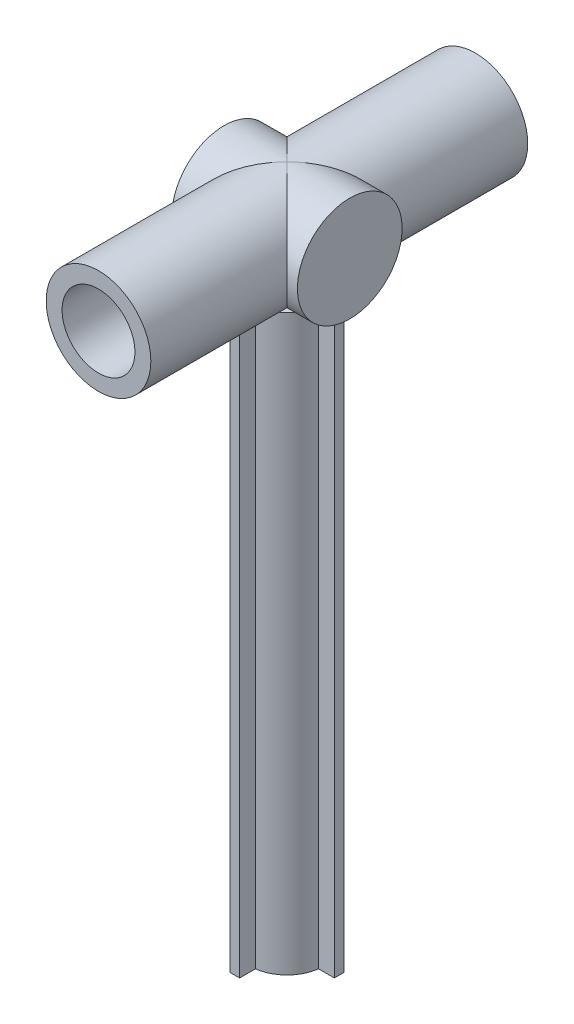
SolidWorks part; units mm, degrees
material "PVC Rigid"
ref_plane "Front Plane" through (0, 0, 0) normal (0, 0, 1) x (1, 0, 0)
ref_plane "Top Plane" through (0, 0, 0) normal (0, 1, 0) x (1, 0, 0)
ref_plane "Right Plane" through (0, 0, 0) normal (1, 0, 0) x (0, 0, -1)
sketch "Sketch3" plane through (0, 0, 0) normal (0, 1, 0) x (1, 0, 0)
  line L4 (-0.5802, 4.407) -> (-0.5802, 6.3234)
  line L5 (0.5802, 4.407) -> (0.5802, 6.3234)
  line L6 (0.5802, 6.3234) -> (-0.5802, 6.3234)
  line L7 (4.407, 0.5802) -> (6.3234, 0.5802)
  line L8 (4.407, -0.5802) -> (6.3234, -0.5802)
  line L9 (6.3234, -0.5802) -> (6.3234, 0.5802)
  line L10 (0.5802, -4.407) -> (0.5802, -6.3234)
  line L11 (0.5802, -6.3234) -> (-0.5802, -6.3234)
  line L12 (-0.5802, -4.407) -> (-0.5802, -6.3234)
  line L13 (-4.407, -0.5802) -> (-6.3234, -0.5802)
  line L14 (-6.3234, -0.5802) -> (-6.3234, 0.5802)
  line L15 (-4.407, 0.5802) -> (-6.3234, 0.5802)
  arc A8 (-0.5802, 4.407) -> (-4.407, 0.5802) centre (0, 0) ccw
  arc A9 (0.5802, 4.407) -> (4.407, 0.5802) centre (0, 0) cw
  arc A10 (4.407, -0.5802) -> (0.5802, -4.407) centre (0, 0) cw
  arc A11 (-0.5802, -4.407) -> (-4.407, -0.5802) centre (0, 0) cw
  circle A12 centre (0, 0) radius 2.794 construction
extrude "Boss-Extrude2" add sketch "Sketch3" along normal blind 69.596
sketch "Sketch4" plane through (0, 69.596, 0) normal (0, 1, 0) x (1, 0, 0)
  circle A0 centre (0, 0) radius 2.794
extrude "Cut-Extrude1" cut sketch "Sketch4" against normal through all
ref_plane "Plane1" through (0, 0, 0) normal (0, 0, 1) x (1, 0, 0)
sketch "Sketch5" plane through (0, 0, 0) normal (0, 0, 1) x (1, 0, 0)
  line L0 (4.407, 69.596) -> (0.5802, 69.596) construction
  circle A0 centre (0, 75.946) radius 6.35
  dimension "D1" = 6.35
  dimension "D2" = 12.7
extrude "Boss-Extrude3" add sketch "Sketch5" along normal blind 22.86 and the other way blind 22.86 separate body
sketch "Sketch6" plane through (0, 0, 22.86) normal (0, 0, 1) x (1, 0, 0)
  circle A0 centre (0, 75.946) radius 3.7382
mirror "Mirror1" about plane through (0, 0, 0) normal (0, 0, 1) of bodies 104 105
extrude "Cut-Extrude3" cut sketch "Sketch6" against normal blind 12.7
mirror "Mirror2" about plane through (0, 0, 0) normal (0, 0, 1) of bodies 107
ref_plane "Plane2" through (0, 0, 0) normal (1, 0, 0) x (0, 0, -1)
sketch "Sketch7" plane through (0, 0, 0) normal (1, 0, 0) x (0, 0, -1)
  line L0 (0, 8.382) -> (0, -8.382) construction
  line L1 (-0.5802, 69.596) -> (-4.407, 69.596) construction
  circle A0 centre (0, 75.946) radius 6.35
  dimension "D1" = 12.7
  dimension "D2" = 6.35
extrude "Boss-Extrude4" add sketch "Sketch7" along normal blind 7.62 and the other way blind 7.62
sketch "Sketch8" plane through (0, 0, 22.86) normal (0, 0, 1) x (1, 0, 0)
  circle A0 centre (0, 75.946) radius 4.4195
  dimension "D1" = 8.839
extrude "Cut-Extrude4" cut sketch "Sketch8" against normal blind 10.16
ref_plane "Plane3" through (0, 0, 0) normal (0, 0, 1) x (1, 0, 0)
sketch "Sketch9" plane through (0, 0, -22.86) normal (0, 0, -1) x (-1, 0, 0)
  circle A0 centre (0, 76.0716) radius 4.4195
  dimension "D1" = 8.839
extrude "Cut-Extrude5" cut sketch "Sketch9" against normal blind 10.16
